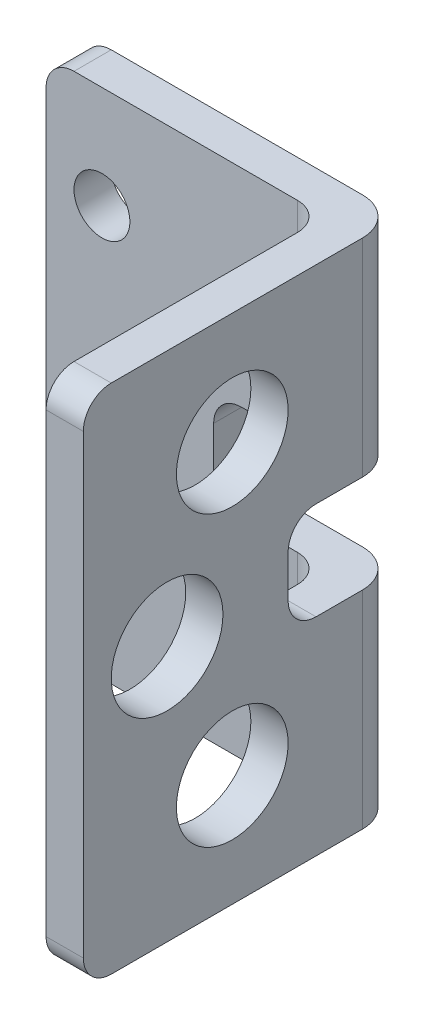
SolidWorks part; units mm, degrees
material "1060 Alloy"
ref_plane "Front Plane" through (0, 0, 0) normal (0, 0, 1) x (1, 0, 0)
ref_plane "Top Plane" through (0, 0, 0) normal (0, 1, 0) x (1, 0, 0)
ref_plane "Right Plane" through (0, 0, 0) normal (1, 0, 0) x (0, 0, -1)
sketch "Sketch1" plane through (0, 0, 0) normal (0, 1, 0) x (1, 0, 0)
  line L1 (0, 0) -> (15, 0)
  line L2 (0, 0) -> (0, 2)
  line L3 (0, 2) -> (15, 2)
  line L6 (15, 0) -> (15, -15)
  line L7 (15, -15) -> (17, -15)
  line L8 (17, 0) -> (17, -15)
  arc A0 (15, 2) -> (17, 0) centre (15, 0) cw
  dimension "D1" = 2
  dimension "D2" = 2
  dimension "D3" = 15
  dimension "D4" = 15
extrude "Boss-Extrude1" add sketch "Sketch1" along normal blind 27.5
sketch "Sketch2" plane through (17, 0, 0) normal (1, 0, 0) x (0, 0, -1)
  line L0 (-15, 0) -> (0, 0) construction
  line L4 (-15, 27.5) -> (-15, 0) construction
  circle A0 centre (-7, 6) radius 3
  circle A1 centre (-10.5, 13.75) radius 3
  circle A2 centre (-7, 21.5) radius 3
  dimension "D1" = 6
  dimension "D2" = 15.5
  dimension "D3" = 6
  dimension "D4" = 7.75
  dimension "D5" = 4.5
  dimension "D6" = 3.5
extrude "Cut-Extrude1" cut sketch "Sketch2" against normal blind 27.5
sketch "Sketch3" plane through (17, 0, 0) normal (1, 0, 0) x (0, 0, -1)
  line L0 (-35.9411, 13.75) -> (1.5605, 13.75) construction
  line L1 (-4, 11.125) -> (2, 11.125)
  line L2 (-4, 11.125) -> (-4, 16.375)
  line L3 (-4, 16.375) -> (2, 16.375)
  line L4 (2, 27.5) -> (2, 0) construction
  line L5 (2, 16.375) -> (2, 11.125)
  circle A0 centre (-10.5, 13.75) radius 3 construction
  point P0 (2, 13.75)
  point P3 (-17.1903, 13.75)
  point P13 (-4, 13.75)
  dimension "D1" = 2.625
  dimension "D2" = 6.5
extrude "Cut-Extrude2" cut sketch "Sketch3" against normal offset from surface (8 mm away) 9 up to face at (0, 13.75, -1)
sketch "Sketch4" plane through (0, 0, -2) normal (0, 0, -1) x (-1, 0, 0)
  line L0 (7.0483, 13.75) -> (-7.0483, 13.75) construction
  line L2 (0, 27.5) -> (0, 0) construction
  line L3 (-15, 0) -> (0, 0) construction
  circle A0 centre (-3, 5.5) radius 1.5
  circle A1 centre (-3, 22) radius 1.5
  point P5 (0, 13.75)
  dimension "D1" = 3
  dimension "D2" = 3
  dimension "D3" = 5.5
extrude "Cut-Extrude3" cut sketch "Sketch4" against normal blind 9
fillet "Fillet1" radius 1.5 10 edges at (15, 21.9375, 0) (15, 5.5625, 0) (16, 0, 15) (0, 0, -1) (0, 27.5, -1) (16, 27.5, 15) (16, 16.375, 4) (9, 16.375, -1) (16, 11.125, 4) (9, 11.125, -1)
